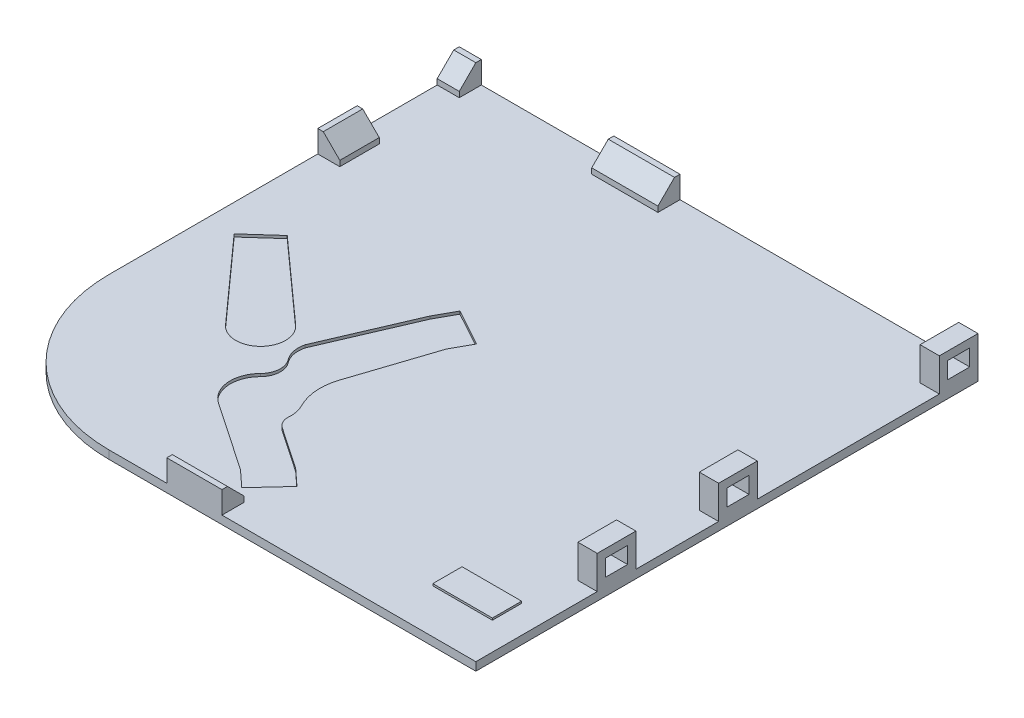
SolidWorks part; units mm, degrees
ref_plane "Спереди" through (0, 0, 0) normal (0, 0, 1) x (1, 0, 0)
ref_plane "Сверху" through (0, 0, 0) normal (0, 1, 0) x (1, 0, 0)
ref_plane "Справа" through (0, 0, 0) normal (1, 0, 0) x (0, 0, -1)
sketch "Эскиз1" plane through (0, 0, 0) normal (0, 1, 0) x (1, 0, 0)
  line L51 (-27.5, 63.5) -> (-27.5, 0)
  line L52 (66.5, 63.5) -> (-27.5, 63.5)
  line L53 (66.5, -27.5) -> (66.5, 63.5)
  line L54 (0, -27.5) -> (66.5, -27.5)
  line L55 (-27.5, 63.5) -> (-27.5, 0)
  line L56 (66.5, 63.5) -> (-27.5, 63.5)
  line L57 (66.5, -27.5) -> (66.5, 63.5)
  line L58 (0, -27.5) -> (66.5, -27.5)
  arc A10 (-27.5, 0) -> (0, -27.5) centre (0, 0) ccw
  arc A11 (-27.5, 0) -> (0, -27.5) centre (0, 0) ccw
  dimension "D1" = 0
extrude "Бобышка-Вытянуть1" add sketch "Эскиз1" along normal blind 1.5
sketch "Эскиз3" plane through (66.5, 0, 0) normal (1, 0, 0) x (0, 0, -1)
  line L0 (1.5, 1.5) -> (1.5, 7.5)
  line L1 (63.5, 1.5) -> (56.5, 1.5)
  line L2 (63.5, 1.5) -> (63.5, 7.5)
  line L3 (63.5, 7.5) -> (56.5, 7.5)
  line L4 (56.5, 1.5) -> (56.5, 7.5)
  line L9 (60, 7.5) -> (60, 1.5) construction
  line L10 (56.5, 4.5) -> (63.5, 4.5) construction
  line L11 (62, 6) -> (58, 6)
  line L12 (58, 3) -> (58, 6)
  line L13 (62, 3) -> (58, 3)
  line L14 (62, 3) -> (62, 6)
  line L15 (23.5, 1.5) -> (16.5, 1.5)
  line L16 (23.5, 1.5) -> (23.5, 7.5)
  line L17 (23.5, 7.5) -> (16.5, 7.5)
  line L18 (16.5, 1.5) -> (16.5, 7.5)
  line L19 (22, 6) -> (18, 6)
  line L20 (18, 3) -> (18, 6)
  line L21 (22, 3) -> (18, 3)
  line L22 (22, 3) -> (22, 6)
  line L23 (-27.5, 1.5) -> (63.5, 1.5) construction
  line L32 (20, 3) -> (20, 6) construction
  line L33 (-2, 3) -> (-2, 6) construction
  line L34 (58.5, 6) -> (58.5, 3) construction
  line L35 (61.5, 6) -> (61.5, 3) construction
  line L36 (18.5, 6) -> (18.5, 3) construction
  line L37 (21.5, 6) -> (21.5, 3) construction
  line L38 (1.5, 1.5) -> (-5.5, 1.5)
  line L39 (-5.5, 1.5) -> (-5.5, 7.5)
  line L40 (1.5, 7.5) -> (-5.5, 7.5)
  line L41 (0, 6) -> (-4, 6)
  line L42 (-4, 3) -> (-4, 6)
  line L43 (0, 3) -> (-4, 3)
  line L44 (0, 3) -> (0, 6)
  line L45 (-0.5, 6) -> (-0.5, 3) construction
  line L46 (-2, 3) -> (-2, 6) construction
  line L47 (-3.5, 6) -> (-3.5, 3) construction
  dimension "D1" = 4
  dimension "D3" = 3
  dimension "D6" = 33
  dimension "D7" = 15
  dimension "D8" = 3
  dimension "D2" = 1.5
  dimension "D4" = 2
  dimension "D5" = 2
extrude "Бобышка-Вытянуть3" add sketch "Эскиз3" against normal blind 3
sketch "Эскиз4" plane through (63.5, 0, 0) normal (-1, 0, 0) x (0, 0, 1)
  line L0 (-56.5, 1.5) -> (-63.5, 1.5) construction
  line L1 (-63.5, 7.5) -> (-56.5, 7.5)
  line L2 (-63.5, 7.5) -> (-63.5, 1.5)
  line L3 (-63.5, 1.5) -> (-56.5, 1.5)
  line L4 (-56.5, 7.5) -> (-56.5, 1.5)
  line L6 (-23.5, 1.5) -> (-16.5, 1.5)
  line L7 (-23.5, 1.5) -> (-23.5, 7.5)
  line L8 (-23.5, 7.5) -> (-16.5, 7.5)
  line L9 (-16.5, 1.5) -> (-16.5, 7.5)
  line L10 (-1.5, 1.5) -> (5.5, 1.5)
  line L11 (-1.5, 1.5) -> (-1.5, 7.5)
  line L12 (-1.5, 7.5) -> (5.5, 7.5)
  line L13 (5.5, 1.5) -> (5.5, 7.5)
extrude "Бобышка-Вытянуть4" add sketch "Эскиз4" along normal blind 0.5
sketch "Эскиз5" plane through (0, 1.5, 0) normal (0, 1, 0) x (1, 0, 0)
  line L0 (-1, 61.5) -> (14, 61.5) construction
  line L1 (-27.5, 63.5) -> (-23.5, 63.5)
  line L2 (-27.5, 63.5) -> (-27.5, 59.5)
  line L3 (-27.5, 59.5) -> (-23.5, 59.5)
  line L4 (-23.5, 63.5) -> (-23.5, 59.5)
  line L5 (43.3, 63.5) -> (-27.5, 63.5) construction
  line L6 (0.5, 63.5) -> (12.5, 63.5)
  line L7 (0.5, 63.5) -> (0.5, 59.5)
  line L8 (0.5, 59.5) -> (12.5, 59.5)
  line L9 (12.5, 63.5) -> (12.5, 59.5)
  line L10 (6.5, 59.5) -> (6.5, 63.5) construction
  line L11 (-25.3, 37.3549) -> (-25.3, 45.5) construction
  line L12 (-25.5, 45.5) -> (38.5, 45.5) construction
  line L13 (-27.5, 63.5) -> (-27.5, 37.3549) construction
  line L14 (-27.5, 45) -> (-23.5, 45)
  line L15 (-27.5, 45) -> (-27.5, 37.8549)
  line L16 (-27.5, 37.8549) -> (-23.5, 37.8549)
  line L17 (-23.5, 45) -> (-23.5, 37.8549)
  line L18 (-27.5, 41.4275) -> (-23.5, 41.4275) construction
  line L20 (10.5, -27.5) -> (20.5, -27.5)
  line L21 (10.5, -27.5) -> (10.5, -23.5)
  line L22 (10.5, -23.5) -> (20.5, -23.5)
  line L23 (20.5, -27.5) -> (20.5, -23.5)
  point P15 (0.5, 61.5)
  point P18 (6.5, 61.5)
  point P32 (-25.3, 41.4275)
  point P33 (19.5, -27.5)
  dimension "D1" = 4
  dimension "D2" = 1.5
  dimension "D3" = 0.5
extrude "Бобышка-Вытянуть5" add sketch "Эскиз5" along normal blind 4
chamfer "Фаска1" distance 3 angle 45 4 edges at (6.5, 5.5, -59.5) (-25.5, 5.5, -59.5) (-23.5, 5.5, -41.4275) (15.5, 5.5, 23.5)
sketch "Эскиз7" plane through (0, 1.5, 0) normal (0, 1, 0) x (1, 0, 0)
  line L4 (-19.6231, 14.4913) -> (-22.5412, 17.7456)
  line L5 (-22.5412, 17.7456) -> (-17.4694, 22.2935)
  line L6 (-17.4694, 22.2935) -> (-14.4913, 19.6231)
  line L7 (8.0953, 22.5935) -> (14.7726, 18.9148) construction
  line L8 (9.951, 4.3049) -> (14.7726, 18.9148)
  line L9 (19.8478, -13.4931) -> (12.2324, -8.315)
  line L10 (2.5672, -10.208) -> (15.0494, -18.6953)
  line L11 (8.0953, 22.5935) -> (1.3022, 6.7828)
  line L12 (9.951, 4.3049) -> (14.7726, 18.9148)
  line L13 (19.8478, -13.4931) -> (12.2324, -8.315)
  line L14 (2.5672, -10.208) -> (15.0494, -18.6953)
  line L15 (8.0953, 22.5935) -> (1.3022, 6.7828)
  line L16 (8.0953, 22.5935) -> (10.0254, 26.097)
  line L17 (14.7726, 18.9148) -> (16.7027, 22.4183)
  line L18 (10.0254, 26.097) -> (16.7027, 22.4183)
  line L19 (15.0494, -18.6953) -> (19.8478, -13.4931) construction
  line L20 (15.0494, -18.6953) -> (17.9897, -21.4073)
  line L21 (19.8478, -13.4931) -> (22.7881, -16.2051)
  line L22 (17.9897, -21.4073) -> (22.7881, -16.2051)
  line L68 (-14.4913, 19.6231) -> (-2.6556, 9.0101)
  line L69 (-9.0101, 2.6556) -> (-19.6231, 14.4913)
  line L70 (-14.4913, 19.6231) -> (-2.6556, 9.0101)
  line L71 (-9.0101, 2.6556) -> (-19.6231, 14.4913)
  arc A16 (14.7726, 18.9148) -> (8.0953, 22.5935) centre (0, 0) ccw
  arc A17 (9.951, 4.3049) -> (10.5437, -3.1305) centre (19.082, 1.2914) ccw
  arc A18 (11.1449, -6.0639) -> (10.5437, -3.1305) centre (5.6598, -5.6598) ccw
  arc A19 (11.1449, -6.0639) -> (12.2324, -8.315) centre (13.6382, -6.2476) ccw
  arc A20 (15.0494, -18.6953) -> (19.8478, -13.4931) centre (0, 0) ccw
  arc A21 (1.7707, -1.7707) -> (2.5672, -10.208) centre (5.6598, -5.6598) ccw
  arc A22 (1.7707, -1.7707) -> (2.0838, 2.9281) centre (-0.7576, 0.7576) ccw
  arc A23 (1.3022, 6.7828) -> (2.0838, 2.9281) centre (5.6598, 5.6598) ccw
  arc A24 (14.7726, 18.9148) -> (8.0953, 22.5935) centre (0, 0) ccw construction
  arc A25 (9.951, 4.3049) -> (10.5437, -3.1305) centre (19.082, 1.2914) ccw
  arc A26 (11.1449, -6.0639) -> (10.5437, -3.1305) centre (5.6598, -5.6598) ccw
  arc A27 (11.1449, -6.0639) -> (12.2324, -8.315) centre (13.6382, -6.2476) ccw
  arc A28 (15.0494, -18.6953) -> (19.8478, -13.4931) centre (0, 0) ccw construction
  arc A29 (1.7707, -1.7707) -> (2.5672, -10.208) centre (5.6598, -5.6598) ccw
  arc A30 (1.7707, -1.7707) -> (2.0838, 2.9281) centre (-0.7576, 0.7576) ccw
  arc A31 (1.3022, 6.7828) -> (2.0838, 2.9281) centre (5.6598, 5.6598) ccw
  arc A53 (-9.0101, 2.6556) -> (-2.6556, 9.0101) centre (-5.6598, 5.6598) ccw
  arc A54 (-9.0101, 2.6556) -> (-2.6556, 9.0101) centre (-5.6598, 5.6598) ccw
  dimension "D3" = 4
  dimension "D1" = 0.5
  dimension "D2" = 0.5
extrude "Вырез-Вытянуть2" cut sketch "Эскиз7" against normal blind 0.5
sketch "Эскиз8" plane through (0, 0, 0) normal (0, 1, 0) x (1, 0, 0)
  line L8 (61.5, -19.5) -> (61.5, -14.2)
  line L9 (50.7, -19.5) -> (61.5, -19.5)
  line L10 (50.7, -14.2) -> (50.7, -19.5)
  line L11 (61.5, -14.2) -> (50.7, -14.2)
  line L12 (61.5, -19.5) -> (61.5, -14.2)
  line L13 (50.7, -19.5) -> (61.5, -19.5)
  line L14 (50.7, -14.2) -> (50.7, -19.5)
  line L15 (61.5, -14.2) -> (50.7, -14.2)
  dimension "D1" = 1
extrude "Бобышка-Вытянуть6" add sketch "Эскиз8" along normal offset from surface (1.85 mm away) 0.15
sketch "Эскиз9" plane through (0, 0, 0) normal (0, 1, 0) x (1, 0, 0)
  line L8 (-27.4, 63.4) -> (-27.4, 0)
  line L9 (66.4, 63.4) -> (-27.4, 63.4)
  line L10 (66.4, -27.4) -> (66.4, 63.4)
  line L11 (0, -27.4) -> (66.4, -27.4)
  line L12 (-27.4, 63.4) -> (-27.4, 0)
  line L13 (66.4, 63.4) -> (-27.4, 63.4)
  line L14 (66.4, -27.4) -> (66.4, 63.4)
  line L15 (0, -27.4) -> (66.4, -27.4)
  line L16 (-27.6, 63.6) -> (-27.6, 0)
  line L17 (66.6, 63.6) -> (-27.6, 63.6)
  line L18 (66.6, -27.6) -> (66.6, 63.6)
  line L19 (0, -27.6) -> (66.6, -27.6)
  line L20 (-27.6, 63.6) -> (-27.6, 0)
  line L21 (66.6, 63.6) -> (-27.6, 63.6)
  line L22 (66.6, -27.6) -> (66.6, 63.6)
  line L23 (0, -27.6) -> (66.6, -27.6)
  arc A2 (-27.4, 0) -> (0, -27.4) centre (0, 0) ccw
  arc A3 (-27.4, 0) -> (0, -27.4) centre (0, 0) ccw
  arc A4 (-27.6, 0) -> (0, -27.6) centre (0, 0) ccw
  arc A5 (-27.6, 0) -> (0, -27.6) centre (0, 0) ccw
  dimension "D1" = 0.1
  dimension "D2" = 0.1
extrude "Вырез-Вытянуть3" [suppressed] cut sketch "Эскиз9" along normal through all
